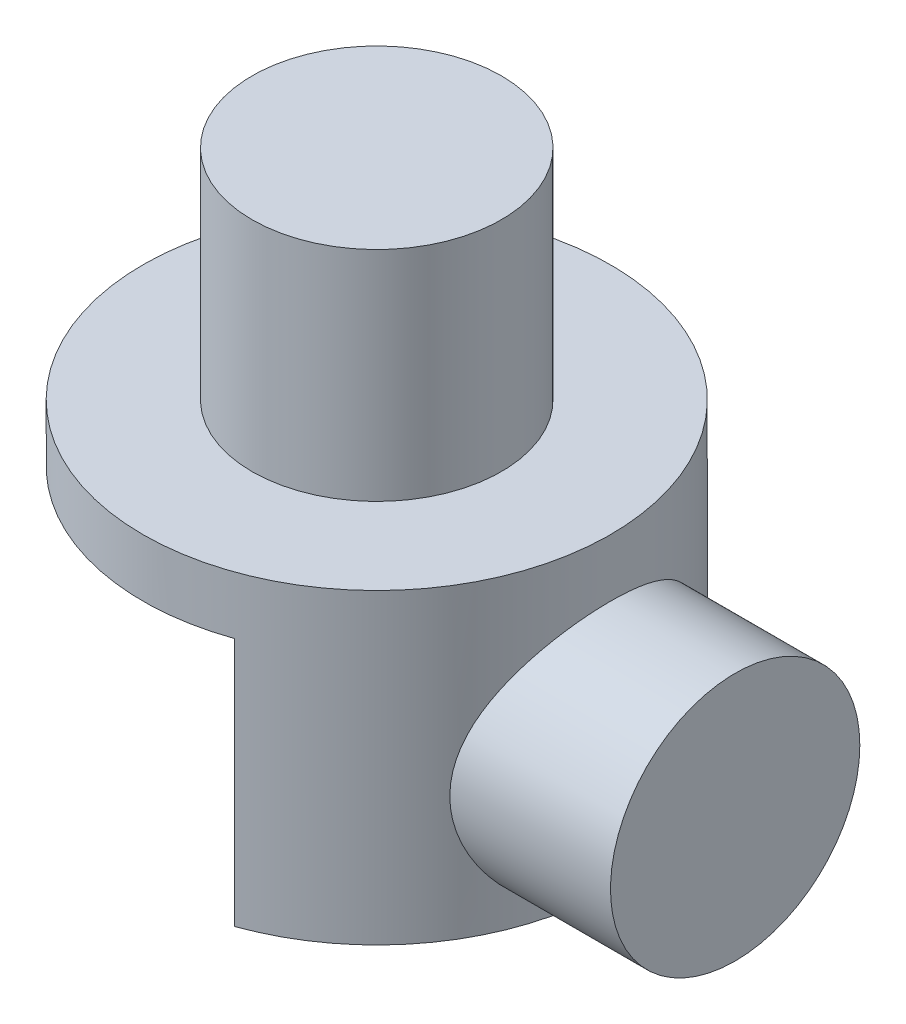
SolidWorks part; units mm, degrees
ref_plane "Front Plane" through (0, 0, 0) normal (0, 0, 1) x (1, 0, 0)
ref_plane "Top Plane" through (0, 0, 0) normal (0, 1, 0) x (1, 0, 0)
ref_plane "Right Plane" through (0, 0, 0) normal (1, 0, 0) x (0, 0, -1)
sketch "Sketch1" plane through (0, 0, 0) normal (0, 1, 0) x (1, 0, 0)
  circle A0 centre (0, 0) radius 7.5
  dimension "D1" = 15
extrude "Boss-Extrude1" add sketch "Sketch1" along normal blind 1.85
sketch "Sketch2" plane through (0, 0, 0) normal (0, -1, 0) x (1, 0, 0)
  line L2 (2.5, 7.0711) -> (2.5, -7.0711)
  arc A3 (2.5, 7.0711) -> (2.5, -7.0711) centre (0, 0) cw
  circle A4 centre (0, 0) radius 7.5 construction
  dimension "D1" = 2.5
extrude "Boss-Extrude2" add sketch "Sketch2" along normal blind 8
sketch "Sketch4" plane through (0, 0, 0) normal (1, 0, 0) x (0, 0, -1)
  line L0 (-7.5, 0) -> (7.5, -8) construction
  line L1 (-7.5, 0) -> (-7.5, 49248.382) construction
  line L3 (7.5, 0) -> (7.5, 50000) construction
  line L5 (-5.6616, -8) -> (49994.3384, -8) construction
  line L7 (-7.0711, -8) -> (7.0711, -8) construction
  circle A0 centre (0, -4) radius 3.5
  dimension "D1" = 7
extrude "Cut-Extrude1" cut sketch "Sketch4" along normal through all
sketch "Sketch5" plane through (2.5, 0, 0) normal (-1, 0, 0) x (0, 0, 1)
  circle A0 centre (0, -4) radius 3.5
  circle A2 centre (0, -4) radius 4
  dimension "D1" = 3.5
extrude "Boss-Extrude3" add sketch "Sketch5" against normal blind 7
sketch "Sketch6" plane through (0, 1.85, 0) normal (0, 1, 0) x (1, 0, 0)
  circle A0 centre (0, 0) radius 4
  dimension "D1" = 4
extrude "Boss-Extrude4" add sketch "Sketch6" along normal blind 7
sketch "Sketch7" plane through (9.5, 0, 0) normal (1, 0, 0) x (0, 0, -1)
  circle A0 centre (0, -4) radius 4 construction
  circle A1 centre (0, -4) radius 4
extrude "Boss-Extrude5" add sketch "Sketch7" along normal blind 2
